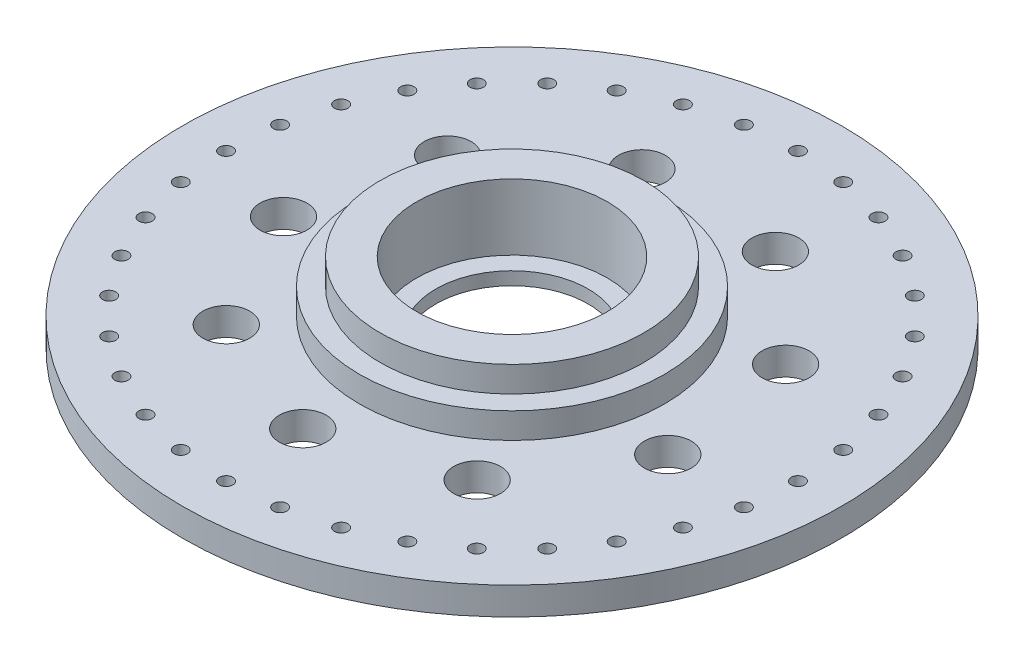
SolidWorks part; units mm, degrees
material "ABS"
ref_plane "Front Plane" through (0, 0, 0) normal (0, 0, 1) x (1, 0, 0)
ref_plane "Top Plane" through (0, 0, 0) normal (0, 1, 0) x (1, 0, 0)
ref_plane "Right Plane" through (0, 0, 0) normal (1, 0, 0) x (0, 0, -1)
sketch "Sketch1" plane through (0, 0, 0) normal (0, 1, 0) x (1, 0, 0)
  circle A0 centre (0, 0) radius 71.374
extrude "Boss-Extrude1" add sketch "Sketch1" along normal blind 5.9944
sketch "Sketch2" plane through (0, 5.9944, 0) normal (0, 1, 0) x (1, 0, 0)
  circle A0 centre (0, 0) radius 20.6502
  circle A1 centre (0, 0) radius 28.575
extrude "Boss-Extrude2" add sketch "Sketch2" along normal blind 11.1252
sketch "Sketch3" plane through (0, 5.9944, 0) normal (0, 1, 0) x (1, 0, 0)
  circle A1 centre (0, 0) radius 20.6502
extrude "Cut-Extrude2" cut sketch "Sketch3" against normal blind 3.175
sketch "Sketch4" plane through (0, 2.8194, 0) normal (0, 1, 0) x (1, 0, 0)
  circle A0 centre (0, 0) radius 16.51
extrude "Cut-Extrude3" cut sketch "Sketch4" against normal through all
sketch "Sketch5" plane through (0, 5.9944, 0) normal (0, 1, 0) x (1, 0, 0)
  circle A0 centre (16.4134, 40.6246) radius 5.08
  circle A3 centre (26.9752, -34.5267) radius 5.08
  circle A4 centre (-1.5291, -43.7883) radius 5.08
  circle A5 centre (-29.318, -32.5609) radius 5.08
  circle A6 centre (-43.3886, -6.0979) radius 5.08
  circle A7 centre (-37.1572, 23.2184) radius 5.08
  circle A8 centre (38.6863, 20.5699) radius 5.08
  circle A9 centre (-13.5396, 41.6705) radius 5.08
  circle A10 centre (42.8575, -9.1097) radius 5.08
  circle A17 centre (38.6863, 20.5699) radius 5.08 [skipped]
  circle A18 centre (42.8575, -9.1097) radius 5.08 [skipped]
  point P18 (0, 0)
  point P19 (0, 0)
  point P26 (0, 0)
  dimension "D1" = 9
extrude "Cut-Extrude4" cut sketch "Sketch5" against normal through all
sketch "Sketch7" plane through (0, 5.9944, 0) normal (0, 1, 0) x (1, 0, 0)
  circle A0 centre (0, 0) radius 28.575
  circle A1 centre (0, 0) radius 33.02
extrude "Boss-Extrude3" add sketch "Sketch7" along normal blind 5.5626
sketch "Sketch8" plane through (0, 5.9944, 0) normal (0, 1, 0) x (1, 0, 0)
  circle A0 centre (-53.6288, 30.9626) radius 1.4478
  circle A2 centre (-47.4375, 39.8048) radius 1.4478
  circle A3 centre (-39.8048, 47.4375) radius 1.4478
  circle A4 centre (-30.9626, 53.6288) radius 1.4478
  circle A5 centre (-21.1797, 58.1907) radius 1.4478
  circle A6 centre (-10.7532, 60.9844) radius 1.4478
  circle A7 centre (0, 61.9252) radius 1.4478
  circle A8 centre (10.7532, 60.9844) radius 1.4478
  circle A9 centre (21.1797, 58.1907) radius 1.4478
  circle A10 centre (30.9626, 53.6288) radius 1.4478
  circle A11 centre (39.8048, 47.4375) radius 1.4478
  circle A12 centre (47.4375, 39.8048) radius 1.4478
  circle A13 centre (53.6288, 30.9626) radius 1.4478
  circle A14 centre (58.1907, 21.1797) radius 1.4478
  circle A15 centre (60.9844, 10.7532) radius 1.4478
  circle A16 centre (61.9252, 0) radius 1.4478
  circle A17 centre (60.9844, -10.7532) radius 1.4478
  circle A18 centre (58.1907, -21.1797) radius 1.4478
  circle A19 centre (53.6288, -30.9626) radius 1.4478
  circle A20 centre (47.4375, -39.8048) radius 1.4478
  circle A21 centre (39.8048, -47.4375) radius 1.4478
  circle A22 centre (30.9626, -53.6288) radius 1.4478
  circle A23 centre (21.1797, -58.1907) radius 1.4478
  circle A24 centre (10.7532, -60.9844) radius 1.4478
  circle A25 centre (0, -61.9252) radius 1.4478
  circle A26 centre (-10.7532, -60.9844) radius 1.4478
  circle A27 centre (-21.1797, -58.1907) radius 1.4478
  circle A28 centre (-30.9626, -53.6288) radius 1.4478
  circle A29 centre (-39.8048, -47.4375) radius 1.4478
  circle A30 centre (-47.4375, -39.8048) radius 1.4478
  circle A31 centre (-53.6288, -30.9626) radius 1.4478
  circle A32 centre (-58.1907, -21.1797) radius 1.4478
  circle A33 centre (-60.9844, -10.7532) radius 1.4478
  circle A34 centre (-61.9252, 0) radius 1.4478
  circle A35 centre (-60.9844, 10.7532) radius 1.4478
  circle A36 centre (-58.1907, 21.1797) radius 1.4478
  point P76 (0, 0)
  dimension "D1" = 36
extrude "Cut-Extrude7" cut sketch "Sketch8" against normal through all
sketch "Sketch9" plane through (0, 5.9944, 0) normal (0, 1, 0) x (1, 0, 0)
  circle A0 centre (38.6863, 20.5699) radius 5.08
  circle A1 centre (42.8575, -9.1097) radius 5.08
extrude "Cut-Extrude8" cut sketch "Sketch9" against normal through all
